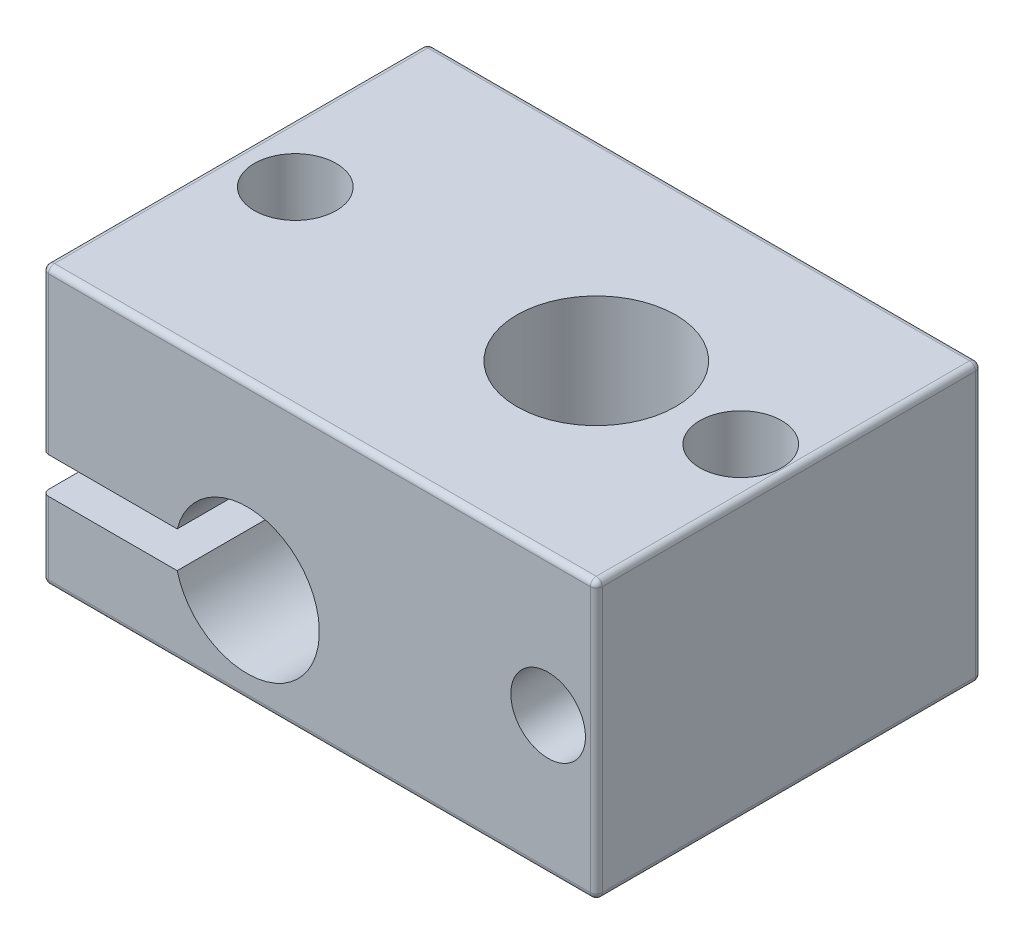
SolidWorks part; units mm, degrees
ref_plane "Front Plane" through (0, 0, 0) normal (0, 0, 1) x (1, 0, 0)
ref_plane "Top Plane" through (0, 0, 0) normal (0, 1, 0) x (1, 0, 0)
ref_plane "Right Plane" through (0, 0, 0) normal (1, 0, 0) x (0, 0, -1)
sketch "Sketch1" plane through (0, 0, 0) normal (0, 1, 0) x (1, 0, 0)
  line L1 (-11.5, -8) -> (11.5, -8)
  line L2 (-11.5, -8) -> (-11.5, 8)
  line L3 (-11.5, 8) -> (11.5, 8)
  line L4 (11.5, -8) -> (11.5, 8)
  line L5 (-11.5, -8) -> (11.5, 8) construction
  line L6 (-11.5, 8) -> (11.5, -8) construction
  point P0 (0, 0)
  dimension "D1" = 23
  dimension "D2" = 16
extrude "Boss-Extrude1" add sketch "Sketch1" along normal blind 11.5
hole_wizard "M6 Clearance Hole3" positions "Sketch5" profile "Sketch6" hole size "M6" standard "ANSI Metric" end condition through all
sketch "Sketch5" plane through (0, 11.5, 0) normal (0, 1, 0) x (1, 0, 0)
  line L0 (11.5, -8) -> (11.5, 8) construction
  line L1 (-11.5, -8) -> (11.5, -8) construction
  point P3 (3.5, 0)
  dimension "D1" = 8
  dimension "D2" = 8
sketch "Sketch6" plane through (3.5, 11.5, 0) normal (1, 0, 0) x (0, 0, 1)
  line L0 (0, 0) -> (0, 11.5)
  line L1 (0, 11.5) -> (3.3, 11.5)
  line L2 (3.3, 11.5) -> (3.3, 0)
  line L5 (3.3, 0) -> (0, 0)
  line L11 (0, -6.35) -> (0, 107.95) construction
  dimension "Thru Hole Dia." = 6.6
  dimension "Thru Hole Depth" = 11.5
hole_wizard "M3 Clearance Hole1" positions "Sketch7" profile "Sketch8" hole size "M3" standard "ANSI Metric" end condition through all
sketch "Sketch7" plane through (0, 11.5, 0) normal (0, 1, 0) x (1, 0, 0)
  line L1 (11.5, -8) -> (11.5, 8) construction
  line L3 (-11.5, -8) -> (11.5, -8) construction
  point P0 (-9, 0)
  point P7 (9.5, 0)
  point P10 (0, 0)
  dimension "D1" = 20.5
  dimension "D2" = 2
  dimension "D3" = 8
sketch "Sketch8" plane through (-9, 11.5, 0) normal (1, 0, 0) x (0, 0, 1)
  line L0 (0, 0) -> (0, 11.5)
  line L1 (0, 11.5) -> (1.7, 11.5)
  line L2 (1.7, 11.5) -> (1.7, 0)
  line L5 (1.7, 0) -> (0, 0)
  line L11 (0, -6.35) -> (0, 107.95) construction
  dimension "Thru Hole Dia." = 3.4
  dimension "Thru Hole Depth" = 11.5
sketch "Sketch9" plane through (0, 0, 8) normal (0, 0, 1) x (1, 0, 0)
  line L1 (-11.5, 0) -> (11.5, 0) construction
  line L2 (11.5, 11.5) -> (11.5, 0) construction
  line L3 (-11.5, 11.5) -> (-11.5, 0) construction
  line L4 (-5.9047, 4.75) -> (-11.5, 4.75)
  line L5 (-5.9047, 4.75) -> (-5.9047, 3.25)
  line L6 (-5.9047, 3.25) -> (-11.5, 3.25)
  line L7 (-11.5, 4.75) -> (-11.5, 3.25)
  line L8 (-5.9047, 4.75) -> (-11.5, 3.25) construction
  line L9 (-5.9047, 3.25) -> (-11.5, 4.75) construction
  line L10 (-3, 4) -> (-6, 4) construction
  circle A0 centre (-3, 4) radius 3
  circle A1 centre (9.5, 5.75) radius 1.55
  point P12 (-8.7024, 4)
  point P16 (-5.9047, 4)
  line M11 (-11.5, 11.5) -> (-11.5, 0)
  dimension "D1" = 6
  dimension "D4" = 3.1
  dimension "D2" = 4
  dimension "D3" = 14.5
  dimension "D5" = 5.75
  dimension "D6" = 2
  dimension "D7" = 1.5
extrude "Cut-Extrude1" cut sketch "Sketch9" against normal through all contours A0 L4 L6 M11 | L5 A0 | A1 | L5 A0
fillet "Fillet1" radius 0.25 14 edges at (0, 0, 8) (-11.5, 0, 0) (0, 0, -8) (11.5, 0, 0) (11.5, 5.75, -8) (-11.5, 8.125, -8) (-11.5, 1.625, -8) (-11.5, 1.625, 8) (-11.5, 8.125, 8) (11.5, 5.75, 8) (11.5, 11.5, 0) (0, 11.5, -8) (-11.5, 11.5, 0) (0, 11.5, 8)
